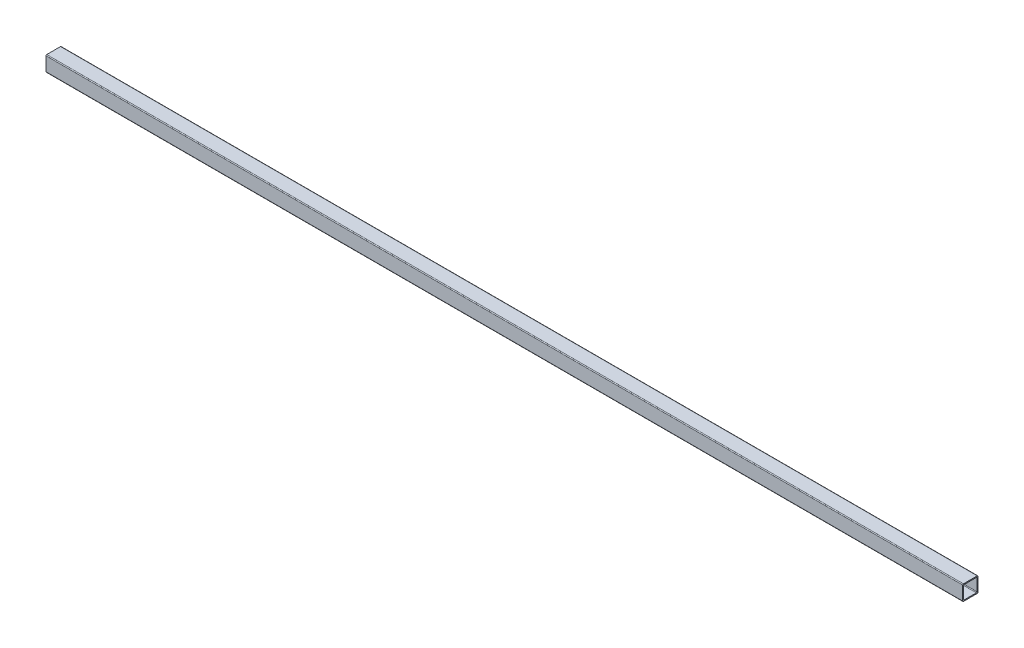
SolidWorks part; units mm, degrees
ref_plane "Front" through (0, 0, 0) normal (0, 0, 1) x (1, 0, 0)
ref_plane "Top" through (0, 0, 0) normal (0, 1, 0) x (1, 0, 0)
ref_plane "Right" through (0, 0, 0) normal (1, 0, 0) x (0, 0, -1)
sketch "Sketch1" plane through (0, 0, 0) normal (1, 0, 0) x (0, 0, -1)
  line L0 (-11.049, 0) -> (-12.7, 0) construction
  line L1 (11.43, -12.7) -> (-11.43, -12.7) construction
  line L2 (12.7, -11.43) -> (12.7, 11.43) construction
  line L3 (11.43, 12.7) -> (-11.43, 12.7) construction
  line L4 (-12.7, -11.43) -> (-12.7, 11.43) construction
  line L5 (12.7, -12.7) -> (-12.7, 12.7) construction
  line L6 (12.7, 12.7) -> (-12.7, -12.7) construction
  line L7 (9.9441, 11.049) -> (-9.9441, 11.049) construction
  line L8 (11.049, 9.9441) -> (11.049, -9.9441) construction
  line L9 (9.9441, -11.049) -> (-9.9441, -11.049) construction
  line L10 (-11.049, 9.9441) -> (-11.049, -9.9441) construction
  line L11 (11.049, 11.049) -> (-11.049, -11.049) construction
  line L12 (11.049, -11.049) -> (-11.049, 11.049) construction
  line L13 (0, -11.049) -> (0, -12.7) construction
  line L14 (11.049, -9.9441) -> (11.049, -12.7) construction
  line L15 (11.049, 0) -> (12.7, 0) construction
  line L16 (11.049, -12.7) -> (12.7, -12.7) construction
  arc A0 (-9.9441, -11.049) -> (-11.049, -9.9441) centre (-9.9441, -9.9441) cw construction
  arc A1 (11.049, -9.9441) -> (9.9441, -11.049) centre (9.9441, -9.9441) cw construction
  arc A2 (9.9441, 11.049) -> (11.049, 9.9441) centre (9.9441, 9.9441) cw construction
  arc A3 (-9.9441, 11.049) -> (-11.049, 9.9441) centre (-9.9441, 9.9441) ccw construction
  arc A4 (11.43, -12.7) -> (12.7, -11.43) centre (11.43, -11.43) ccw construction
  arc A5 (12.7, 11.43) -> (11.43, 12.7) centre (11.43, 11.43) ccw construction
  arc A6 (-11.43, 12.7) -> (-12.7, 11.43) centre (-11.43, 11.43) ccw construction
  arc A7 (-11.43, -12.7) -> (-12.7, -11.43) centre (-11.43, -11.43) cw construction
  point P0 (0, 0)
  point P6 (0, 0)
  dimension "D2" = 1.1049
  dimension "D3" = 1.27
  dimension "Outside Width" = 25.4
  dimension "Ouside Height" = 25.4
  dimension "Inside Height" = 22.098
  dimension "Wall Thickness" = 1.651
sketch "Sketch2" plane through (0, 0, 0) normal (0, 0, 1) x (1, 0, 0)
  line L0 (-762, 0) -> (762, 0) construction
  point P3 (-738.251, 0)
  point P4 (738.251, 0)
  dimension "Length" = 1524
  dimension "D1" = 23.749
  dimension "D2" = 23.749
sketch "Sketch4" plane through (0, 0, 0) normal (1, 0, 0) x (0, 0, -1)
  line L8 (12.7, -11.43) -> (12.7, 11.43)
  line L9 (11.43, 12.7) -> (-11.43, 12.7)
  line L10 (-12.7, -11.43) -> (-12.7, 11.43)
  line L11 (11.43, -12.7) -> (-11.43, -12.7)
  line L12 (11.049, 9.9441) -> (11.049, -9.9441)
  line L13 (9.9441, -11.049) -> (-9.9441, -11.049)
  line L14 (-11.049, 9.9441) -> (-11.049, -9.9441)
  line L15 (9.9441, 11.049) -> (-9.9441, 11.049)
  arc A8 (12.7, 11.43) -> (11.43, 12.7) centre (11.43, 11.43) ccw
  arc A9 (-11.43, 12.7) -> (-12.7, 11.43) centre (-11.43, 11.43) ccw
  arc A10 (-12.7, -11.43) -> (-11.43, -12.7) centre (-11.43, -11.43) ccw
  arc A11 (11.43, -12.7) -> (12.7, -11.43) centre (11.43, -11.43) ccw
  arc A12 (9.9441, -11.049) -> (11.049, -9.9441) centre (9.9441, -9.9441) ccw
  arc A13 (-11.049, -9.9441) -> (-9.9441, -11.049) centre (-9.9441, -9.9441) ccw
  arc A14 (-9.9441, 11.049) -> (-11.049, 9.9441) centre (-9.9441, 9.9441) ccw
  arc A15 (11.049, 9.9441) -> (9.9441, 11.049) centre (9.9441, 9.9441) ccw
extrude "Boss-Extrude1" add sketch "Sketch4" along normal up to vertex (762 mm away) and the other way up to vertex (762 mm away)
equation "\"D3@Sketch1\"=\"Outside Width@Sketch1\"*.05"
equation "\"D2@Sketch1\" = \"Inside Height@Sketch1\" * .05"
equation "\"D1@Sketch2\"=\"Outside Width@Sketch1\"-\"Wall Thickness@Sketch1\""
equation "\"D2@Sketch2\"=\"D1@Sketch2\""
